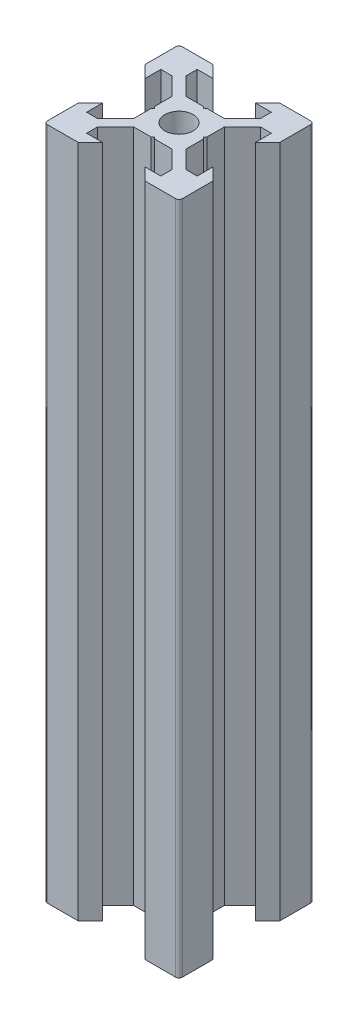
SolidWorks part; units mm, degrees
material "6063-O，挤压棒材(SS)"
ref_plane "前视基准面" through (0, 0, 0) normal (0, 0, 1) x (1, 0, 0)
ref_plane "上视基准面" through (0, 0, 0) normal (0, 1, 0) x (1, 0, 0)
ref_plane "右视基准面" through (0, 0, 0) normal (1, 0, 0) x (0, 0, -1)
other "Configuration Table"
sketch "草图1" plane through (0, 0, 0) normal (0, 1, 0) x (1, 0, 0)
  line L0 (-2.0109, 3.9) -> (2.0109, 3.9)
  line L1 (3.4251, 4.4858) -> (5.5, 6.5607)
  line L2 (5.5, 6.5607) -> (5.5, 8.2)
  line L3 (5.5, 8.2) -> (3.3, 8.2)
  line L4 (3.1, 8.4) -> (3.1, 9.3)
  line L5 (3.8, 10) -> (8.5, 10)
  line L6 (10, 8.5) -> (10, 3.8)
  line L7 (9.3, 3.1) -> (8.4, 3.1)
  line L8 (8.2, 3.3) -> (8.2, 5.5)
  line L9 (8.2, 5.5) -> (6.5607, 5.5)
  line L10 (6.5607, 5.5) -> (4.4858, 3.4251)
  line L11 (3.9, 2.0109) -> (3.9, -2.0109)
  line L12 (4.4858, -3.4251) -> (6.5607, -5.5)
  line L13 (6.5607, -5.5) -> (8.2, -5.5)
  line L14 (8.2, -5.5) -> (8.2, -3.3)
  line L15 (8.4, -3.1) -> (9.3, -3.1)
  line L16 (10, -3.8) -> (10, -8.5)
  line L17 (8.5, -10) -> (3.8, -10)
  line L18 (3.1, -9.3) -> (3.1, -8.4)
  line L19 (3.3, -8.2) -> (5.5, -8.2)
  line L20 (5.5, -8.2) -> (5.5, -6.5607)
  line L21 (5.5, -6.5607) -> (3.4251, -4.4858)
  line L22 (2.0109, -3.9) -> (-2.0109, -3.9)
  line L23 (-3.4251, -4.4858) -> (-5.5, -6.5607)
  line L24 (-5.5, -6.5607) -> (-5.5, -8.2)
  line L25 (-5.5, -8.2) -> (-3.3, -8.2)
  line L26 (-3.1, -8.4) -> (-3.1, -9.3)
  line L27 (-3.8, -10) -> (-8.5, -10)
  line L28 (-10, -8.5) -> (-10, -3.8)
  line L29 (-9.3, -3.1) -> (-8.4, -3.1)
  line L30 (-8.2, -3.3) -> (-8.2, -5.5)
  line L31 (-8.2, -5.5) -> (-6.5607, -5.5)
  line L32 (-6.5607, -5.5) -> (-4.4858, -3.4251)
  line L33 (-3.9, -2.0109) -> (-3.9, 2.0109)
  line L34 (-4.4858, 3.4251) -> (-6.5607, 5.5)
  line L35 (-6.5607, 5.5) -> (-8.2, 5.5)
  line L36 (-8.2, 5.5) -> (-8.2, 3.3)
  line L37 (-8.4, 3.1) -> (-9.3, 3.1)
  line L38 (-10, 3.8) -> (-10, 8.5)
  line L39 (-8.5, 10) -> (-3.8, 10)
  line L40 (-3.1, 9.3) -> (-3.1, 8.4)
  line L41 (-3.3, 8.2) -> (-5.5, 8.2)
  line L42 (-5.5, 8.2) -> (-5.5, 6.5607)
  line L43 (-5.5, 6.5607) -> (-3.4251, 4.4858)
  line L44 (-4.4858, 3.4251) -> (-3.4251, 4.4858) construction
  line L45 (3.4251, 4.4858) -> (4.4858, 3.4251) construction
  line L46 (4.4858, -3.4251) -> (3.4251, -4.4858) construction
  line L47 (-3.4251, -4.4858) -> (-4.4858, -3.4251) construction
  line L48 (3.9555, -3.9555) -> (-3.9555, 3.9555) construction
  line L49 (3.9555, 3.9555) -> (-3.9555, -3.9555) construction
  line L50 (-9.5, 3.3) -> (-9.5, 3.6)
  line L51 (-9.5, 3.6) -> (-9.8, 3.6)
  line L52 (-3.6, 9.8) -> (-3.6, 9.5)
  line L53 (-3.6, 9.5) -> (-3.3, 9.5)
  line L54 (3.3, 9.5) -> (3.6, 9.5)
  line L55 (3.6, 9.5) -> (3.6, 9.8)
  line L56 (9.5, 3.3) -> (9.5, 3.6)
  line L57 (9.5, 3.6) -> (9.8, 3.6)
  line L58 (9.5, -3.3) -> (9.5, -3.6)
  line L59 (9.5, -3.6) -> (9.8, -3.6)
  line L60 (3.3, -9.5) -> (3.6, -9.5)
  line L61 (3.6, -9.5) -> (3.6, -9.8)
  line L62 (-3.6, -9.8) -> (-3.6, -9.5)
  line L63 (-3.6, -9.5) -> (-3.3, -9.5)
  line L64 (-9.5, -3.3) -> (-9.5, -3.6)
  line L65 (-9.5, -3.6) -> (-9.8, -3.6)
  arc A1 (2.0109, 3.9) -> (3.4251, 4.4858) centre (2.0109, 5.9) ccw
  arc A2 (3.3, 8.2) -> (3.1, 8.4) centre (3.3, 8.4) cw
  arc A5 (8.5, 10) -> (10, 8.5) centre (8.5, 8.5) cw
  arc A8 (8.4, 3.1) -> (8.2, 3.3) centre (8.4, 3.3) cw
  arc A9 (4.4858, 3.4251) -> (3.9, 2.0109) centre (5.9, 2.0109) ccw
  arc A10 (3.9, -2.0109) -> (4.4858, -3.4251) centre (5.9, -2.0109) ccw
  arc A11 (8.2, -3.3) -> (8.4, -3.1) centre (8.4, -3.3) cw
  arc A14 (10, -8.5) -> (8.5, -10) centre (8.5, -8.5) cw
  arc A17 (3.1, -8.4) -> (3.3, -8.2) centre (3.3, -8.4) cw
  arc A18 (3.4251, -4.4858) -> (2.0109, -3.9) centre (2.0109, -5.9) ccw
  arc A19 (-2.0109, -3.9) -> (-3.4251, -4.4858) centre (-2.0109, -5.9) ccw
  arc A20 (-3.3, -8.2) -> (-3.1, -8.4) centre (-3.3, -8.4) cw
  arc A23 (-8.5, -10) -> (-10, -8.5) centre (-8.5, -8.5) cw
  arc A26 (-8.4, -3.1) -> (-8.2, -3.3) centre (-8.4, -3.3) cw
  arc A27 (-4.4858, -3.4251) -> (-3.9, -2.0109) centre (-5.9, -2.0109) ccw
  arc A28 (-3.9, 2.0109) -> (-4.4858, 3.4251) centre (-5.9, 2.0109) ccw
  arc A29 (-8.2, 3.3) -> (-8.4, 3.1) centre (-8.4, 3.3) cw
  arc A32 (-10, 8.5) -> (-8.5, 10) centre (-8.5, 8.5) cw
  arc A35 (-3.1, 8.4) -> (-3.3, 8.2) centre (-3.3, 8.4) cw
  arc A36 (-3.4251, 4.4858) -> (-2.0109, 3.9) centre (-2.0109, 5.9) ccw
  arc A37 (-9.3, 3.1) -> (-9.5, 3.3) centre (-9.3, 3.3) cw
  arc A39 (-3.8, 10) -> (-3.6, 9.8) centre (-3.8, 9.8) cw
  arc A40 (-3.3, 9.5) -> (-3.1, 9.3) centre (-3.3, 9.3) cw
  arc A41 (3.1, 9.3) -> (3.3, 9.5) centre (3.3, 9.3) cw
  arc A42 (3.6, 9.8) -> (3.8, 10) centre (3.8, 9.8) cw
  arc A43 (9.3, 3.1) -> (9.5, 3.3) centre (9.3, 3.3) ccw
  arc A44 (9.8, 3.6) -> (10, 3.8) centre (9.8, 3.8) ccw
  arc A45 (9.3, -3.1) -> (9.5, -3.3) centre (9.3, -3.3) cw
  arc A46 (9.8, -3.6) -> (10, -3.8) centre (9.8, -3.8) cw
  arc A47 (3.1, -9.3) -> (3.3, -9.5) centre (3.3, -9.3) ccw
  arc A48 (3.6, -9.8) -> (3.8, -10) centre (3.8, -9.8) ccw
  arc A49 (-3.8, -10) -> (-3.6, -9.8) centre (-3.8, -9.8) ccw
  arc A50 (-3.3, -9.5) -> (-3.1, -9.3) centre (-3.3, -9.3) ccw
  arc A51 (-9.3, -3.1) -> (-9.5, -3.3) centre (-9.3, -3.3) ccw
  arc A53 (-9.8, 3.6) -> (-10, 3.8) centre (-9.8, 3.8) cw
  arc A54 (-9.8, -3.6) -> (-10, -3.8) centre (-9.8, -3.8) ccw
  circle A55 centre (0, 0) radius 2.075
  point P119 (3.9, 0)
  dimension "D2" = 1.5
  dimension "D4" = 6.2
  dimension "D8" = 2
  dimension "D10" = 4.15
  dimension "D11" = 0.2
  dimension "D1" = 20
  dimension "D3" = 1.5
  dimension "D5" = 7.2
  dimension "D6" = 1.8
  dimension "D7" = 11
  dimension "D9" = 7.8
extrude "2020L" [suppressed] add sketch "草图1" along normal blind 100
hole_wizard "1-2020M5" [suppressed] positions "草图2" profile "草图3" tap size "M5" standard "GB"
sketch "草图2" [suppressed] plane through (0, 0, 0) normal (0, -1, 0) x (-1, 0, 0)
  point P0 (0, 0)
sketch "草图3" plane through (0, 0, 0) normal (1, 0, 0) x (0, 0, -1)
  line L0 (0, 0) -> (0, 13.6618)
  line L1 (0, 13.6618) -> (2.1, 12.4)
  line L2 (2.1, 12.4) -> (2.1, 0)
  line L5 (2.1, 0) -> (0, 0)
  line L10 (0, 13.6618) -> (-2.1, 12.4) construction
  line L11 (0, -6.35) -> (0, 107.95) construction
  dimension "螺纹孔钻头直径" = 4.2
  dimension "螺纹孔钻头深度" = 12.4
  dimension "导头角度" = 118
cosmetic thread "孔螺蚊线1" [suppressed] parameters "D1"=10, "D2"=5.2
hole_wizard "2-2020M5" [suppressed] positions "草图5" profile "草图6" tap size "M5" standard "GB"
sketch "草图5" [suppressed] plane through (0, 100, 0) normal (0, 1, 0) x (1, 0, 0)
  point P0 (0, 0)
sketch "草图6" plane through (0, 100, 0) normal (1, 0, 0) x (0, 0, 1)
  line L0 (0, 0) -> (0, 13.6618)
  line L1 (0, 13.6618) -> (2.1, 12.4)
  line L2 (2.1, 12.4) -> (2.1, 0)
  line L5 (2.1, 0) -> (0, 0)
  line L10 (0, 13.6618) -> (-2.1, 12.4) construction
  line L11 (0, -6.35) -> (0, 107.95) construction
  dimension "螺纹孔钻头直径" = 4.2
  dimension "螺纹孔钻头深度" = 12.4
  dimension "导头角度" = 118
cosmetic thread "孔螺蚊线2" [suppressed] parameters "D1"=10, "D2"=5
sketch "草图7" plane through (0, 0, 0) normal (0, 1, 0) x (1, 0, 0)
  line L88 (-10, 0) -> (10, 0) construction
  line L89 (-13.9555, 3.9555) -> (-6.0445, -3.9555) construction
  line L90 (-13.9555, -3.9555) -> (-6.0445, 3.9555) construction
  line L91 (6.0445, 3.9555) -> (13.9555, -3.9555) construction
  line L92 (6.0445, -3.9555) -> (13.9555, 3.9555) construction
  line L93 (-7.9891, 3.9) -> (-12.0109, 3.9)
  line L94 (-13.4251, 4.4858) -> (-15.5, 6.5607)
  line L95 (-15.5, 6.5607) -> (-15.5, 8.2)
  line L96 (-15.5, 8.2) -> (-13.1, 8.2)
  line L97 (-13.1, 8.2) -> (-13.1, 9.5)
  line L98 (-13.1, 9.5) -> (-13.6, 9.5)
  line L99 (-13.6, 9.5) -> (-13.6, 10)
  line L100 (-13.6, 10) -> (-18.5, 10)
  line L101 (-20, 8.5) -> (-20, 3.6)
  line L102 (-20, 3.6) -> (-19.5, 3.6)
  line L103 (-19.5, 3.6) -> (-19.5, 3.1)
  line L104 (-19.5, 3.1) -> (-18.2, 3.1)
  line L105 (-18.2, 3.1) -> (-18.2, 5.5)
  line L106 (-18.2, 5.5) -> (-16.5607, 5.5)
  line L107 (-16.5607, 5.5) -> (-14.4858, 3.4251)
  line L108 (-13.9, 2.0109) -> (-13.9, -2.0109)
  line L109 (-14.4858, -3.4251) -> (-16.5607, -5.5)
  line L110 (-16.5607, -5.5) -> (-18.2, -5.5)
  line L111 (-18.2, -5.5) -> (-18.2, -3.1)
  line L112 (-18.2, -3.1) -> (-19.5, -3.1)
  line L113 (-19.5, -3.1) -> (-19.5, -3.6)
  line L114 (-19.5, -3.6) -> (-20, -3.6)
  line L115 (-20, -3.6) -> (-20, -8.5)
  line L116 (-18.5, -10) -> (-13.6, -10)
  line L117 (-13.6, -10) -> (-13.6, -9.5)
  line L118 (-13.6, -9.5) -> (-13.1, -9.5)
  line L119 (-13.1, -9.5) -> (-13.1, -8.2)
  line L120 (-13.1, -8.2) -> (-15.5, -8.2)
  line L121 (-15.5, -8.2) -> (-15.5, -6.5607)
  line L122 (-15.5, -6.5607) -> (-13.4251, -4.4858)
  line L123 (-12.0109, -3.9) -> (-7.9891, -3.9)
  line L124 (-6.5749, -4.4858) -> (-4.5, -6.5607)
  line L125 (-4.5, -6.5607) -> (-4.5, -8.2)
  line L126 (-4.5, -8.2) -> (-6.9, -8.2)
  line L127 (-6.9, -8.2) -> (-6.9, -9.5)
  line L128 (-6.9, -9.5) -> (-6.4, -9.5)
  line L129 (-6.4, -9.5) -> (-6.4, -10)
  line L130 (-6.4, -10) -> (6.4, -10)
  line L131 (6.4, -10) -> (6.4, -9.5)
  line L132 (6.4, -9.5) -> (6.9, -9.5)
  line L133 (6.9, -9.5) -> (6.9, -8.2)
  line L134 (6.9, -8.2) -> (4.5, -8.2)
  line L135 (4.5, -8.2) -> (4.5, -6.5607)
  line L136 (4.5, -6.5607) -> (6.5749, -4.4858)
  line L137 (7.9891, -3.9) -> (12.0109, -3.9)
  line L138 (13.4251, -4.4858) -> (15.5, -6.5607)
  line L139 (15.5, -6.5607) -> (15.5, -8.2)
  line L140 (15.5, -8.2) -> (13.1, -8.2)
  line L141 (13.1, -8.2) -> (13.1, -9.5)
  line L142 (13.1, -9.5) -> (13.6, -9.5)
  line L143 (13.6, -9.5) -> (13.6, -10)
  line L144 (13.6, -10) -> (18.5, -10)
  line L145 (20, -8.5) -> (20, -3.6)
  line L146 (20, -3.6) -> (19.5, -3.6)
  line L147 (19.5, -3.6) -> (19.5, -3.1)
  line L148 (19.5, -3.1) -> (18.2, -3.1)
  line L149 (18.2, -3.1) -> (18.2, -5.5)
  line L150 (18.2, -5.5) -> (16.5607, -5.5)
  line L151 (16.5607, -5.5) -> (14.4858, -3.4251)
  line L152 (13.9, -2.0109) -> (13.9, 2.0109)
  line L153 (14.4858, 3.4251) -> (16.5607, 5.5)
  line L154 (16.5607, 5.5) -> (18.2, 5.5)
  line L155 (18.2, 5.5) -> (18.2, 3.1)
  line L156 (18.2, 3.1) -> (19.5, 3.1)
  line L157 (19.5, 3.1) -> (19.5, 3.6)
  line L158 (19.5, 3.6) -> (20, 3.6)
  line L159 (20, 3.6) -> (20, 8.5)
  line L160 (18.5, 10) -> (13.6, 10)
  line L161 (13.6, 10) -> (13.6, 9.5)
  line L162 (13.6, 9.5) -> (13.1, 9.5)
  line L163 (13.1, 9.5) -> (13.1, 8.2)
  line L164 (13.1, 8.2) -> (15.5, 8.2)
  line L165 (15.5, 8.2) -> (15.5, 6.5607)
  line L166 (15.5, 6.5607) -> (13.4251, 4.4858)
  line L167 (12.0109, 3.9) -> (7.9891, 3.9)
  line L168 (6.5749, 4.4858) -> (4.5, 6.5607)
  line L169 (4.5, 6.5607) -> (4.5, 8.2)
  line L170 (4.5, 8.2) -> (6.9, 8.2)
  line L171 (6.9, 8.2) -> (6.9, 9.5)
  line L172 (6.9, 9.5) -> (6.4, 9.5)
  line L173 (6.4, 9.5) -> (6.4, 10)
  line L174 (6.4, 10) -> (-6.4, 10)
  line L175 (-6.4, 10) -> (-6.4, 9.5)
  line L176 (-6.4, 9.5) -> (-6.9, 9.5)
  line L177 (-6.9, 9.5) -> (-6.9, 8.2)
  line L178 (-6.9, 8.2) -> (-4.5, 8.2)
  line L179 (-4.5, 8.2) -> (-4.5, 6.5607)
  line L180 (-4.5, 6.5607) -> (-6.5749, 4.4858)
  line L181 (-14.4858, 3.4251) -> (-13.4251, 4.4858) construction
  line L182 (-14.4858, -3.4251) -> (-13.4251, -4.4858) construction
  line L183 (13.4251, -4.4858) -> (14.4858, -3.4251) construction
  line L184 (13.4251, 4.4858) -> (14.4858, 3.4251) construction
  line L185 (-2.3787, 8.2) -> (2.3787, 8.2)
  line L186 (2.3787, 8.2) -> (2.3787, 6.5607)
  line L187 (2.3787, 6.5607) -> (5.5142, 3.4251)
  line L188 (6.1, 2.0109) -> (6.1, -2.0109)
  line L189 (5.5142, -3.4251) -> (2.3787, -6.5607)
  line L190 (2.3787, -6.5607) -> (2.3787, -8.2)
  line L191 (2.3787, -8.2) -> (-2.3787, -8.2)
  line L192 (-2.3787, -8.2) -> (-2.3787, -6.5607)
  line L193 (-2.3787, -6.5607) -> (-5.5142, -3.4251)
  line L194 (-6.1, -2.0109) -> (-6.1, 2.0109)
  line L195 (-5.5142, 3.4251) -> (-2.3787, 6.5607)
  line L196 (-2.3787, 6.5607) -> (-2.3787, 8.2)
  line L197 (-6.5749, 4.4858) -> (-5.5142, 3.4251) construction
  line L198 (-6.5749, -4.4858) -> (-5.5142, -3.4251) construction
  line L199 (5.5142, 3.4251) -> (6.5749, 4.4858) construction
  line L200 (5.5142, -3.4251) -> (6.5749, -4.4858) construction
  arc A16 (-12.0109, 3.9) -> (-13.4251, 4.4858) centre (-12.0109, 5.9) cw
  arc A17 (-18.5, 10) -> (-20, 8.5) centre (-18.5, 8.5) ccw
  arc A18 (-14.4858, 3.4251) -> (-13.9, 2.0109) centre (-15.9, 2.0109) cw
  arc A19 (-13.9, -2.0109) -> (-14.4858, -3.4251) centre (-15.9, -2.0109) cw
  arc A20 (-20, -8.5) -> (-18.5, -10) centre (-18.5, -8.5) ccw
  arc A21 (-13.4251, -4.4858) -> (-12.0109, -3.9) centre (-12.0109, -5.9) cw
  arc A22 (-7.9891, -3.9) -> (-6.5749, -4.4858) centre (-7.9891, -5.9) cw
  arc A23 (6.5749, -4.4858) -> (7.9891, -3.9) centre (7.9891, -5.9) cw
  arc A24 (12.0109, -3.9) -> (13.4251, -4.4858) centre (12.0109, -5.9) cw
  arc A25 (18.5, -10) -> (20, -8.5) centre (18.5, -8.5) ccw
  arc A26 (14.4858, -3.4251) -> (13.9, -2.0109) centre (15.9, -2.0109) cw
  arc A27 (13.9, 2.0109) -> (14.4858, 3.4251) centre (15.9, 2.0109) cw
  arc A28 (20, 8.5) -> (18.5, 10) centre (18.5, 8.5) ccw
  arc A29 (13.4251, 4.4858) -> (12.0109, 3.9) centre (12.0109, 5.9) cw
  arc A30 (7.9891, 3.9) -> (6.5749, 4.4858) centre (7.9891, 5.9) cw
  arc A31 (-6.5749, 4.4858) -> (-7.9891, 3.9) centre (-7.9891, 5.9) cw
  arc A32 (5.5142, 3.4251) -> (6.1, 2.0109) centre (4.1, 2.0109) cw
  arc A33 (6.1, -2.0109) -> (5.5142, -3.4251) centre (4.1, -2.0109) cw
  arc A34 (-5.5142, -3.4251) -> (-6.1, -2.0109) centre (-4.1, -2.0109) cw
  arc A35 (-6.1, 2.0109) -> (-5.5142, 3.4251) centre (-4.1, 2.0109) cw
  circle A36 centre (-10, 0) radius 2.075
  circle A37 centre (10, 0) radius 2.075
  point P177 (0, 10)
  point P178 (0, -10)
  dimension "D5" = 2
  dimension "D8" = 1.5
  dimension "D13" = 4.15
  dimension "D1" = 20
  dimension "D2" = 45
  dimension "D3" = 45
  dimension "D4" = 7.8
  dimension "D6" = 1.5
  dimension "D7" = 40
  dimension "D9" = 6.2
  dimension "D10" = 7.2
  dimension "D11" = 1.8
  dimension "D12" = 11
extrude "2040L" [suppressed] add sketch "草图7" along normal blind 100
fillet "圆角1" [suppressed] radius 0.25
sketch "草图8" [suppressed] plane through (0, 0, 0) normal (0, -1, 0) x (1, 0, 0)
  circle A0 centre (10, 0) radius 2.075 construction
  circle A1 centre (-10, 0) radius 2.075 construction
  point P0 (-10, 0)
  point P1 (10, 0)
hole_wizard "1-2040M5" [suppressed] positions "草图13" profile "草图14" tap size "M5" standard "GB"
sketch "草图13" [suppressed] plane through (0, 0, 0) normal (0, -1, 0) x (-1, 0, 0)
  point P0 (-10, 0)
sketch "草图14" plane through (10, 0, 0) normal (1, 0, 0) x (0, 0, -1)
  line L0 (0, 0) -> (0, 13.6618)
  line L1 (0, 13.6618) -> (2.1, 12.4)
  line L2 (2.1, 12.4) -> (2.1, 0)
  line L5 (2.1, 0) -> (0, 0)
  line L10 (0, 13.6618) -> (-2.1, 12.4) construction
  line L11 (0, -6.35) -> (0, 107.95) construction
  dimension "螺纹孔钻头直径" = 4.2
  dimension "螺纹孔钻头深度" = 12.4
  dimension "导头角度" = 118
cosmetic thread "孔螺蚊线7" [suppressed] parameters "D1"=10, "D2"=5
hole_wizard "2-2040M5" [suppressed] positions "草图15" profile "草图16" tap size "M5" standard "GB"
sketch "草图15" [suppressed] plane through (0, 0, 0) normal (0, -1, 0) x (-1, 0, 0)
  point P0 (10, 0)
sketch "草图16" plane through (-10, 0, 0) normal (1, 0, 0) x (0, 0, -1)
  line L0 (0, 0) -> (0, 13.6618)
  line L1 (0, 13.6618) -> (2.1, 12.4)
  line L2 (2.1, 12.4) -> (2.1, 0)
  line L5 (2.1, 0) -> (0, 0)
  line L10 (0, 13.6618) -> (-2.1, 12.4) construction
  line L11 (0, -6.35) -> (0, 107.95) construction
  dimension "螺纹孔钻头直径" = 4.2
  dimension "螺纹孔钻头深度" = 12.4
  dimension "导头角度" = 118
cosmetic thread "孔螺蚊线8" [suppressed] parameters "D1"=10, "D2"=5
hole_wizard "3-2040M5" [suppressed] positions "草图19" profile "草图20" tap size "M5" standard "GB"
sketch "草图19" [suppressed] plane through (0, 100, 0) normal (0, 1, 0) x (1, 0, 0)
  point P0 (10, 0)
sketch "草图20" plane through (10, 100, 0) normal (1, 0, 0) x (0, 0, 1)
  line L0 (0, 0) -> (0, 13.6618)
  line L1 (0, 13.6618) -> (2.1, 12.4)
  line L2 (2.1, 12.4) -> (2.1, 0)
  line L5 (2.1, 0) -> (0, 0)
  line L10 (0, 13.6618) -> (-2.1, 12.4) construction
  line L11 (0, -6.35) -> (0, 107.95) construction
  dimension "螺纹孔钻头直径" = 4.2
  dimension "螺纹孔钻头深度" = 12.4
  dimension "导头角度" = 118
cosmetic thread "孔螺蚊线10" [suppressed] parameters "D1"=10, "D2"=5
hole_wizard "4-2040M5" [suppressed] positions "草图21" profile "草图22" tap size "M5" standard "GB"
sketch "草图21" [suppressed] plane through (0, 100, 0) normal (0, 1, 0) x (1, 0, 0)
  point P0 (-10, 0)
sketch "草图22" plane through (-10, 100, 0) normal (1, 0, 0) x (0, 0, 1)
  line L0 (0, 0) -> (0, 13.6618)
  line L1 (0, 13.6618) -> (2.1, 12.4)
  line L2 (2.1, 12.4) -> (2.1, 0)
  line L5 (2.1, 0) -> (0, 0)
  line L10 (0, 13.6618) -> (-2.1, 12.4) construction
  line L11 (0, -6.35) -> (0, 107.95) construction
  dimension "螺纹孔钻头直径" = 4.2
  dimension "螺纹孔钻头深度" = 12.4
  dimension "导头角度" = 118
cosmetic thread "孔螺蚊线11" [suppressed] parameters "D1"=10, "D2"=5
sketch "草图23" plane through (0, 0, 0) normal (0, 1, 0) x (1, 0, 0)
  line L0 (-3.9, 2.0109) -> (-3.9, -2.0109)
  line L1 (-4.4858, -3.4251) -> (-6.5607, -5.5)
  line L2 (-6.5607, -5.5) -> (-8.2, -5.5)
  line L3 (-8.2, -5.5) -> (-8.2, -3.1)
  line L4 (-8.2, -3.1) -> (-9.5, -3.1)
  line L5 (-9.5, -3.1) -> (-9.5, -3.6)
  line L6 (-9.5, -3.6) -> (-10, -3.6)
  line L7 (-10, -3.6) -> (-10, -8.5)
  line L8 (-8.5, -10) -> (-3.6, -10)
  line L9 (-3.6, -10) -> (-3.6, -9.5)
  line L10 (-3.6, -9.5) -> (-3.1, -9.5)
  line L11 (-3.1, -9.5) -> (-3.1, -8.2)
  line L12 (-3.1, -8.2) -> (-5.5, -8.2)
  line L13 (-5.5, -8.2) -> (-5.5, -6.5607)
  line L14 (-5.5, -6.5607) -> (-3.4251, -4.4858)
  line L15 (-2.0109, -3.9) -> (2.0109, -3.9)
  line L16 (3.4251, -4.4858) -> (5.5, -6.5607)
  line L17 (5.5, -6.5607) -> (5.5, -8.2)
  line L18 (5.5, -8.2) -> (3.1, -8.2)
  line L19 (3.1, -8.2) -> (3.1, -9.5)
  line L20 (3.1, -9.5) -> (3.6, -9.5)
  line L21 (3.6, -9.5) -> (3.6, -10)
  line L22 (3.6, -10) -> (8.5, -10)
  line L23 (-10, 8.5) -> (-10, 3.6)
  line L24 (-10, 3.6) -> (-9.5, 3.6)
  line L25 (-9.5, 3.6) -> (-9.5, 3.1)
  line L26 (-9.5, 3.1) -> (-8.2, 3.1)
  line L27 (-8.2, 3.1) -> (-8.2, 5.5)
  line L28 (-8.2, 5.5) -> (-6.5607, 5.5)
  line L29 (-6.5607, 5.5) -> (-4.4858, 3.4251)
  line L30 (-3.9555, -3.9555) -> (3.9555, 3.9555) construction
  line L31 (-3.9555, 3.9555) -> (3.9555, -3.9555) construction
  line L32 (-4.4858, -3.4251) -> (-3.4251, -4.4858) construction
  line L39 (-4.4858, 3.4251) -> (-3.4251, 4.4858) construction
  line L40 (3.4251, -4.4858) -> (4.4858, -3.4251) construction
  line L41 (-3.4251, 4.4858) -> (-5.5, 6.5607)
  line L42 (-5.5, 6.5607) -> (-5.5, 8.2332)
  line L43 (2.6122, 3.9) -> (-2.0109, 3.9)
  line L44 (3.9, 2.6122) -> (3.9, -2.0109)
  line L45 (6.5607, -5.5) -> (8.2332, -5.5)
  line L46 (4.4858, -3.4251) -> (6.5607, -5.5)
  arc A0 (-3.9, -2.0109) -> (-4.4858, -3.4251) centre (-5.9, -2.0109) cw
  arc A1 (-10, -8.5) -> (-8.5, -10) centre (-8.5, -8.5) ccw
  arc A2 (-3.4251, -4.4858) -> (-2.0109, -3.9) centre (-2.0109, -5.9) cw
  arc A3 (2.0109, -3.9) -> (3.4251, -4.4858) centre (2.0109, -5.9) cw
  arc A4 (8.5, -10) -> (10, -8.5) centre (8.5, -8.5) ccw
  arc A5 (10, -8.5) -> (-8.5, 10) centre (-8.5, -8.5) ccw
  arc A6 (-8.5, 10) -> (-10, 8.5) centre (-8.5, 8.5) ccw
  arc A7 (-4.4858, 3.4251) -> (-3.9, 2.0109) centre (-5.9, 2.0109) cw
  arc A14 (-5.5, 8.2332) -> (2.7444, 4.25) centre (-8.5, -8.5) cw
  arc A15 (2.7444, 4.25) -> (2.6122, 3.9) centre (2.6122, 4.1) cw
  arc A16 (-2.0109, 3.9) -> (-3.4251, 4.4858) centre (-2.0109, 5.9) cw
  arc A17 (4.25, 2.7444) -> (3.9, 2.6122) centre (4.1, 2.6122) ccw
  arc A18 (8.2332, -5.5) -> (4.25, 2.7444) centre (-8.5, -8.5) ccw
  arc A19 (3.9, -2.0109) -> (4.4858, -3.4251) centre (5.9, -2.0109) ccw
  circle A20 centre (0, 0) radius 2.075
  dimension "D3" = 1.5
  dimension "D5" = 2
  dimension "D10" = 17
  dimension "D11" = 0.2
  dimension "D12" = 4.15
  dimension "D1" = 20
  dimension "D2" = 1.5
  dimension "D4" = 11
  dimension "D6" = 1.8
  dimension "D7" = 3.9
  dimension "D8" = 6.2
  dimension "D9" = 7.2
extrude "2020R" [suppressed] add sketch "草图23" along normal blind 100
fillet "圆角2" [suppressed] radius 0.25
hole_wizard "1-2020R" [suppressed] positions "草图24" profile "草图25" tap size "M5" standard "GB"
sketch "草图24" [suppressed] plane through (0, 100, 0) normal (0, 1, 0) x (1, 0, 0)
  point P0 (0, 0)
sketch "草图25" plane through (0, 100, 0) normal (1, 0, 0) x (0, 0, 1)
  line L0 (0, 0) -> (0, 13.6618)
  line L1 (0, 13.6618) -> (2.1, 12.4)
  line L2 (2.1, 12.4) -> (2.1, 0)
  line L5 (2.1, 0) -> (0, 0)
  line L10 (0, 13.6618) -> (-2.1, 12.4) construction
  line L11 (0, -6.35) -> (0, 107.95) construction
  dimension "螺纹孔钻头直径" = 4.2
  dimension "螺纹孔钻头深度" = 12.4
  dimension "导头角度" = 118
cosmetic thread "孔螺蚊线12" parameters "D1"=10, "D2"=5
hole_wizard "2-2020R" [suppressed] positions "草图26" profile "草图27" tap size "M5" standard "GB"
sketch "草图26" [suppressed] plane through (0, 0, 0) normal (0, -1, 0) x (-1, 0, 0)
  point P0 (0, 0)
sketch "草图27" plane through (0, 0, 0) normal (1, 0, 0) x (0, 0, -1)
  line L0 (0, 0) -> (0, 13.6618)
  line L1 (0, 13.6618) -> (2.1, 12.4)
  line L2 (2.1, 12.4) -> (2.1, 0)
  line L5 (2.1, 0) -> (0, 0)
  line L10 (0, 13.6618) -> (-2.1, 12.4) construction
  line L11 (0, -6.35) -> (0, 107.95) construction
  dimension "螺纹孔钻头直径" = 4.2
  dimension "螺纹孔钻头深度" = 12.4
  dimension "导头角度" = 118
cosmetic thread "孔螺蚊线13" parameters "D1"=10, "D2"=5
sketch "草图28" plane through (0, 0, 0) normal (0, 1, 0) x (1, 0, 0)
  line L56 (-3.9, 2.8393) -> (-3.9, 0.2828)
  line L57 (-3.9, 0.2828) -> (-3.6172, 0)
  line L58 (-3.6172, 0) -> (-3.9, -0.2828)
  line L59 (-3.9, -0.2828) -> (-3.9, -2.8393)
  line L60 (-3.9, -2.8393) -> (-6.5607, -5.5)
  line L61 (-6.5607, -5.5) -> (-8.2, -5.5)
  line L62 (-8.2, -5.5) -> (-8.2, -3.15)
  line L63 (-8.2, -3.15) -> (-10, -4.95)
  line L64 (-10, -4.95) -> (-10, -9.5)
  line L65 (-9.5, -10) -> (-4.95, -10)
  line L66 (-4.95, -10) -> (-3.15, -8.2)
  line L67 (-3.15, -8.2) -> (-5.5, -8.2)
  line L68 (-5.5, -8.2) -> (-5.5, -6.5607)
  line L69 (-5.5, -6.5607) -> (-2.8393, -3.9)
  line L70 (-2.8393, -3.9) -> (-0.2828, -3.9)
  line L71 (-0.2828, -3.9) -> (0, -3.6172)
  line L72 (0, -3.6172) -> (0.2828, -3.9)
  line L73 (0.2828, -3.9) -> (2.8393, -3.9)
  line L74 (2.8393, -3.9) -> (5.5, -6.5607)
  line L75 (5.5, -6.5607) -> (5.5, -8.2)
  line L76 (5.5, -8.2) -> (3.15, -8.2)
  line L77 (3.15, -8.2) -> (4.95, -10)
  line L78 (4.95, -10) -> (9.5, -10)
  line L79 (10, -9.5) -> (10, -4.95)
  line L80 (10, -4.95) -> (8.2, -3.15)
  line L81 (8.2, -3.15) -> (8.2, -5.5)
  line L82 (8.2, -5.5) -> (6.5607, -5.5)
  line L83 (6.5607, -5.5) -> (3.9, -2.8393)
  line L84 (3.9, -2.8393) -> (3.9, -0.2828)
  line L85 (3.9, -0.2828) -> (3.6172, 0)
  line L86 (3.6172, 0) -> (3.9, 0.2828)
  line L87 (3.9, 0.2828) -> (3.9, 2.8393)
  line L88 (3.9, 2.8393) -> (6.5607, 5.5)
  line L89 (6.5607, 5.5) -> (8.2, 5.5)
  line L90 (8.2, 5.5) -> (8.2, 3.15)
  line L91 (8.2, 3.15) -> (10, 4.95)
  line L92 (10, 4.95) -> (10, 9.5)
  line L93 (9.5, 10) -> (4.95, 10)
  line L94 (4.95, 10) -> (3.15, 8.2)
  line L95 (3.15, 8.2) -> (5.5, 8.2)
  line L96 (5.5, 8.2) -> (5.5, 6.5607)
  line L97 (5.5, 6.5607) -> (2.8393, 3.9)
  line L98 (2.8393, 3.9) -> (0.2828, 3.9)
  line L99 (0.2828, 3.9) -> (0, 3.6172)
  line L100 (0, 3.6172) -> (-0.2828, 3.9)
  line L101 (-0.2828, 3.9) -> (-2.8393, 3.9)
  line L102 (-2.8393, 3.9) -> (-5.5, 6.5607)
  line L103 (-5.5, 6.5607) -> (-5.5, 8.2)
  line L104 (-5.5, 8.2) -> (-3.15, 8.2)
  line L105 (-3.15, 8.2) -> (-4.95, 10)
  line L106 (-4.95, 10) -> (-9.5, 10)
  line L107 (-10, 9.5) -> (-10, 4.95)
  line L108 (-10, 4.95) -> (-8.2, 3.15)
  line L109 (-8.2, 3.15) -> (-8.2, 5.5)
  line L110 (-8.2, 5.5) -> (-6.5607, 5.5)
  line L111 (-6.5607, 5.5) -> (-3.9, 2.8393)
  line L112 (-2.8393, 3.9) -> (-3.9, 2.8393) construction
  line L113 (-3.9, -2.8393) -> (-2.8393, -3.9) construction
  line L114 (2.8393, -3.9) -> (3.9, -2.8393) construction
  line L115 (2.8393, 3.9) -> (3.9, 2.8393) construction
  line L116 (-3.3697, 3.3697) -> (3.3697, -3.3697) construction
  line L117 (-3.3697, -3.3697) -> (3.3697, 3.3697) construction
  arc A4 (-10, -9.5) -> (-9.5, -10) centre (-9.5, -9.5) ccw
  arc A5 (9.5, -10) -> (10, -9.5) centre (9.5, -9.5) ccw
  arc A6 (10, 9.5) -> (9.5, 10) centre (9.5, 9.5) ccw
  arc A7 (-9.5, 10) -> (-10, 9.5) centre (-9.5, 9.5) ccw
  circle A8 centre (0, 0) radius 2.075
  dimension "D7" = 0.5
  dimension "D9" = 4.15
  dimension "D1" = 7.8
  dimension "D2" = 20
  dimension "D3" = 1.5
  dimension "D4" = 0.4
  dimension "D5" = 11
  dimension "D6" = 6.3
  dimension "D8" = 1.8
extrude "2020V" add sketch "草图28" along normal blind 100
hole_wizard "1-2020V" positions "草图29" profile "草图30" tap size "M5" standard "GB"
sketch "草图29" plane through (0, 100, 0) normal (0, 1, 0) x (1, 0, 0)
  point P0 (0, 0)
sketch "草图30" plane through (0, 100, 0) normal (1, 0, 0) x (0, 0, 1)
  line L0 (0, 0) -> (0, 13.6618)
  line L1 (0, 13.6618) -> (2.1, 12.4)
  line L2 (2.1, 12.4) -> (2.1, 0)
  line L5 (2.1, 0) -> (0, 0)
  line L10 (0, 13.6618) -> (-2.1, 12.4) construction
  line L11 (0, -6.35) -> (0, 107.95) construction
  dimension "螺纹孔钻头直径" = 4.2
  dimension "螺纹孔钻头深度" = 12.4
  dimension "导头角度" = 118
cosmetic thread "孔螺蚊线14" parameters "D1"=10, "D2"=5
hole_wizard "2-2020V" positions "草图31" profile "草图32" tap size "M5" standard "GB"
sketch "草图31" plane through (0, 0, 0) normal (0, -1, 0) x (-1, 0, 0)
  point P0 (0, 0)
sketch "草图32" plane through (0, 0, 0) normal (1, 0, 0) x (0, 0, -1)
  line L0 (0, 0) -> (0, 13.6618)
  line L1 (0, 13.6618) -> (2.1, 12.4)
  line L2 (2.1, 12.4) -> (2.1, 0)
  line L5 (2.1, 0) -> (0, 0)
  line L10 (0, 13.6618) -> (-2.1, 12.4) construction
  line L11 (0, -6.35) -> (0, 107.95) construction
  dimension "螺纹孔钻头直径" = 4.2
  dimension "螺纹孔钻头深度" = 12.4
  dimension "导头角度" = 118
cosmetic thread "孔螺蚊线15" parameters "D1"=10, "D2"=5
equation "\"L\"= 100mm'型材长度"
equation "\"L@2020L\" = \"L\""
equation "\"L@2040L\" = \"L\""
equation "\"L@2020R\"= \"L\""
equation "\"L@2020V\"= \"L\""
